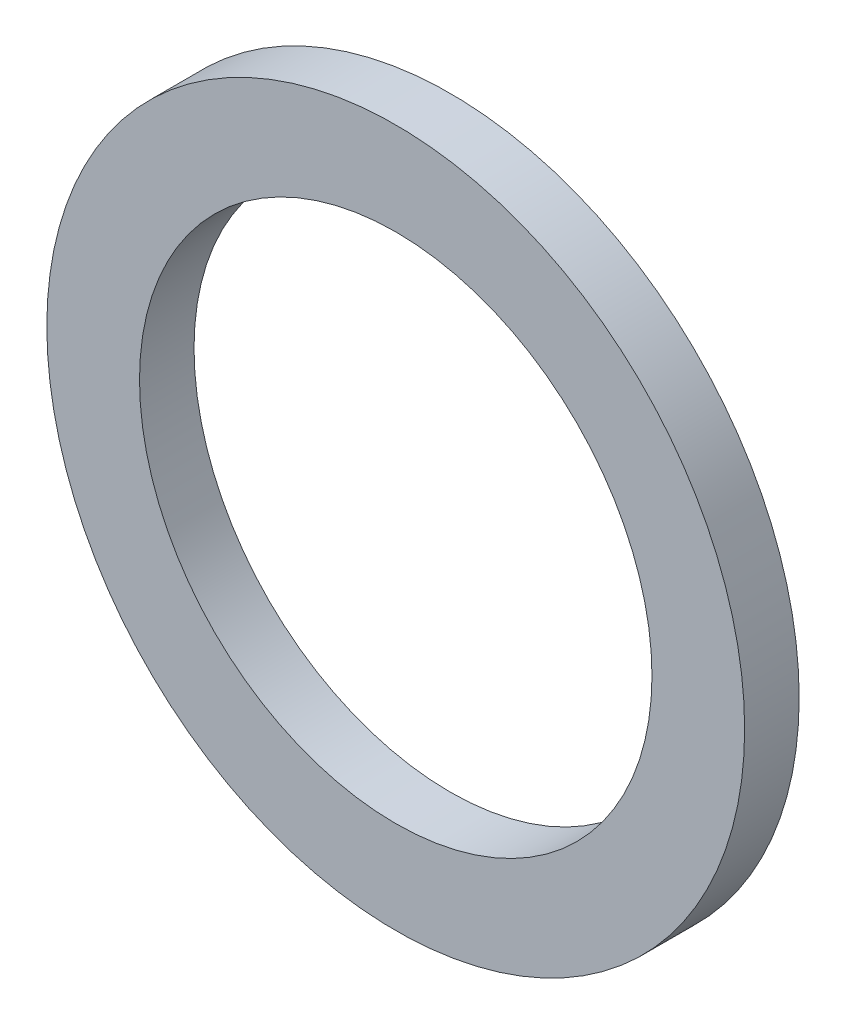
SolidWorks part; units mm, degrees
ref_plane "前视基准面" through (0, 0, 0) normal (0, 0, 1) x (1, 0, 0)
ref_plane "上视基准面" through (0, 0, 0) normal (0, 1, 0) x (1, 0, 0)
ref_plane "右视基准面" through (0, 0, 0) normal (1, 0, 0) x (0, 0, -1)
sketch "草图1" plane through (0, 0, 0) normal (0, 0, 1) x (1, 0, 0)
  circle A0 centre (0, 0) radius 2.35
  circle A1 centre (0, 0) radius 3.2
  dimension "D1" = 4.7
  dimension "D2" = 6.4
extrude "凸台-拉伸1" add sketch "草图1" along normal blind 0.5
